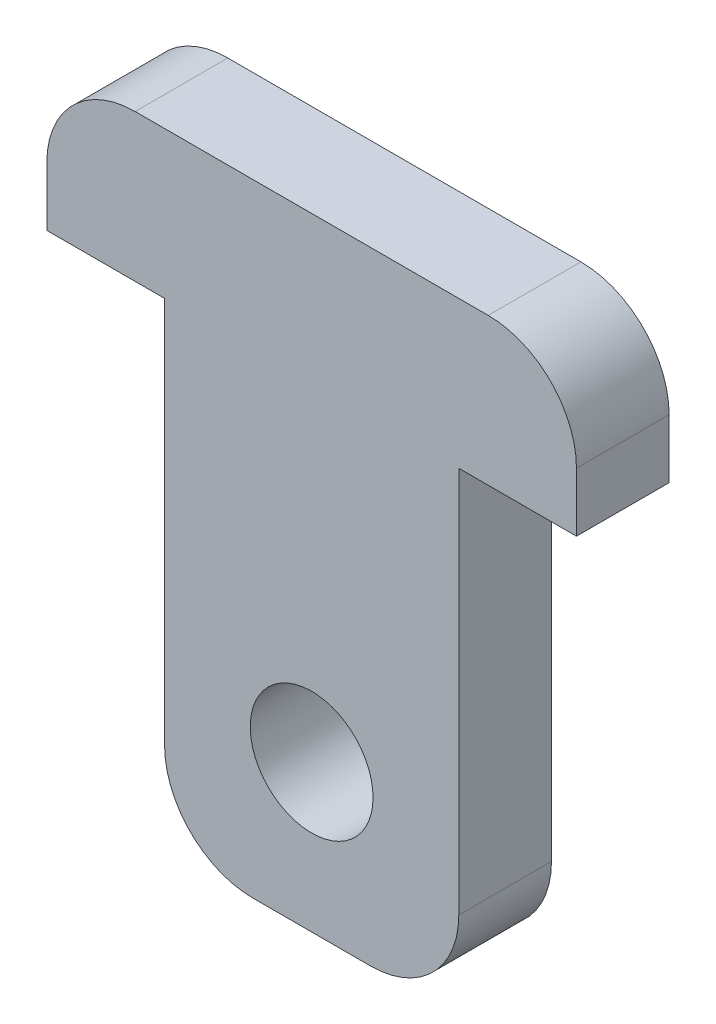
SolidWorks part; units mm, degrees
material "Hexcel AS4C (3000 Filaments)"
ref_plane "Front Plane" through (0, 0, 0) normal (0, 0, 1) x (1, 0, 0)
ref_plane "Top Plane" through (0, 0, 0) normal (0, 1, 0) x (1, 0, 0)
ref_plane "Right Plane" through (0, 0, 0) normal (1, 0, 0) x (0, 0, -1)
sketch "Sketch1" plane through (0, 0, 0) normal (0, 0, 1) x (1, 0, 0)
  line L0 (0, 0) -> (5.08, 0)
  line L1 (5.08, 0) -> (5.08, -16.7)
  line L2 (8.89, -20.51) -> (13.97, -20.51)
  line L3 (17.78, -16.7) -> (17.78, 0)
  line L4 (17.78, 0) -> (22.86, 0)
  line L5 (22.86, 0) -> (22.86, 2.54)
  line L6 (19.05, 6.35) -> (3.81, 6.35)
  line L7 (0, 2.54) -> (0, 0)
  line L8 (5.08, -4) -> (17.78, -4) construction
  circle A0 centre (11.43, -14.16) radius 2.65
  arc A1 (3.81, 6.35) -> (0, 2.54) centre (3.81, 2.54) ccw
  arc A2 (22.86, 2.54) -> (19.05, 6.35) centre (19.05, 2.54) ccw
  arc A3 (13.97, -20.51) -> (17.78, -16.7) centre (13.97, -16.7) ccw
  arc A4 (5.08, -16.7) -> (8.89, -20.51) centre (8.89, -16.7) ccw
  point P13 (0, 0)
  point P14 (11.43, -20.51)
  point P17 (0, 6.35)
  dimension "D7" = 5.3
  dimension "D8" = 3.81
  dimension "D1" = 12.7
  dimension "D2" = 5.08
  dimension "D3" = 6.35
  dimension "D4" = 4
  dimension "D5" = 10.16
  dimension "D6" = 6.35
extrude "Boss-Extrude1" add sketch "Sketch1" along normal blind 4
